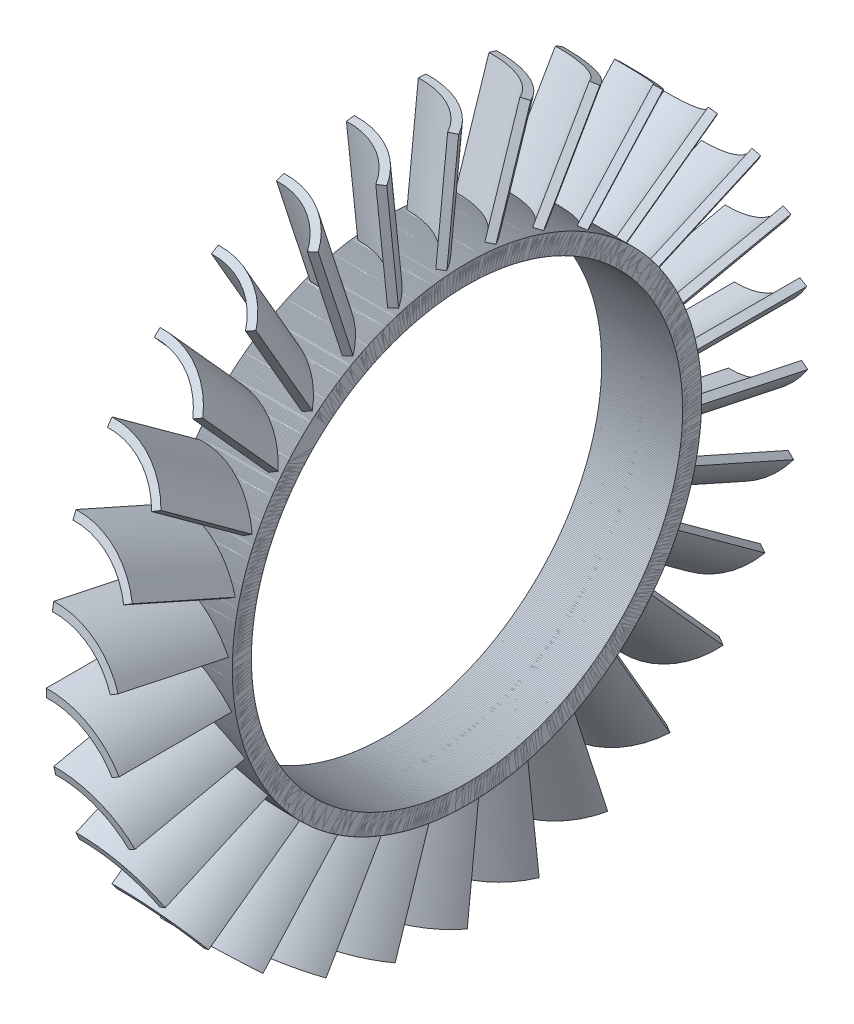
SolidWorks part; units mm, degrees
ref_plane "Front Plane" through (0, 0, 0) normal (0, 0, 1) x (1, 0, 0)
ref_plane "Top Plane" through (0, 0, 0) normal (0, 1, 0) x (1, 0, 0)
ref_plane "Right Plane" through (0, 0, 0) normal (1, 0, 0) x (0, 0, -1)
sketch "Sketch1" plane through (0, 0, 0) normal (1, 0, 0) x (0, 0, -1)
  circle A0 centre (0, 0) radius 58
  circle A1 centre (0, 0) radius 53
  dimension "D1" = 106
  dimension "D2" = 116
extrude "Boss-Extrude1" add sketch "Sketch1" along normal mid plane 20
sketch "Sketch2" plane through (0, 0, 0) normal (0, 0, 1) x (1, 0, 0)
  line L0 (-10.9263, 0) -> (10, 0) construction
  line L1 (10, -58) -> (10, 58) construction
  line L2 (0, 58) -> (0, -58.9597) construction
  line L3 (10, 58) -> (-10, 58) construction
  line L5 (-10, 58) -> (-10, -58) construction
  arc A0 (-9, 0) -> (9, -10) centre (-8.3385, -20.0093) cw
  point P9 (-9, 0)
  point P10 (9, -10)
  dimension "D1" = 1
  dimension "D2" = 1
  dimension "D3" = 10
extrude "Extrude-Thin1" add sketch "Sketch2" along normal blind 85 thin
sketch "Sketch3" plane through (0, 0, 0) normal (1, 0, 0) x (0, 0, -1)
  circle A0 centre (0, 0.0109) radius 53
  dimension "D1" = 106
sketch "Sketch5" plane through (0, 0, 0) normal (1, 0, 0) x (0, 0, -1)
  circle A0 centre (0, 0) radius 53.3261
extrude "Cut-Extrude2" cut sketch "Sketch5" against normal mid plane 85
pattern_circular "CirPattern2" count 30 over 360 about axis through (0, 0, 0) along (1, 0, 0) of bodies 104
